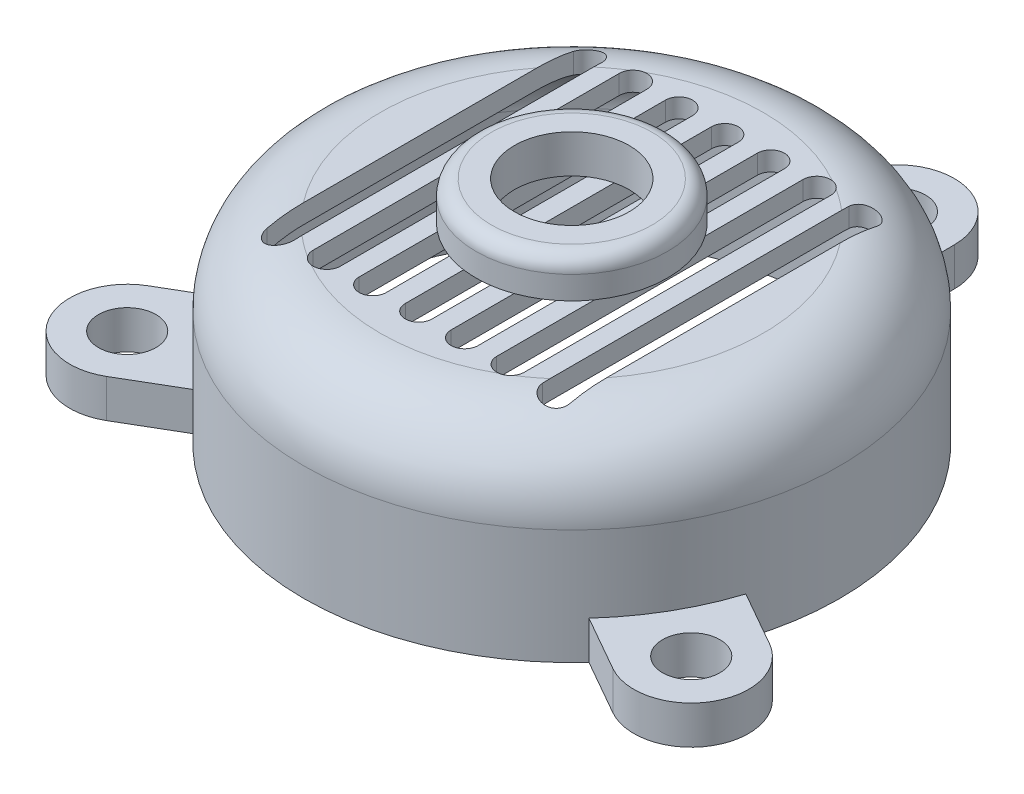
SolidWorks part; units mm, degrees
ref_plane "Front Plane" through (0, 0, 0) normal (0, 0, 1) x (1, 0, 0)
ref_plane "Top Plane" through (0, 0, 0) normal (0, 1, 0) x (1, 0, 0)
ref_plane "Right Plane" through (0, 0, 0) normal (1, 0, 0) x (0, 0, -1)
sketch "Sketch1" plane through (0, 0, 0) normal (0, 1, 0) x (1, 0, 0)
  circle A0 centre (0, 0) radius 3.5
  dimension "D1" = 7
extrude "Boss-Extrude1" add sketch "Sketch1" along normal mid plane 2.5
fillet "Fillet1" radius 1 1 edges at (0, 1.25, 3.5)
shell "Shell1" thickness 0.25
sketch "Sketch2" plane through (0, 1.25, 0) normal (0, 1, 0) x (1, 0, 0)
  line L0 (0, 2) -> (0, -2) construction
  line L1 (0.175, 2) -> (0.175, -2)
  line L2 (-0.175, 2) -> (-0.175, -2)
  line L3 (0.6, 2) -> (0.6, -2) construction
  line L4 (0.7768, 2) -> (0.7768, -2)
  line L5 (0.4232, 2) -> (0.4232, -2)
  line L6 (1.2, 2) -> (1.2, -2) construction
  line L7 (1.38, 2) -> (1.38, -2)
  line L8 (1.02, 2) -> (1.02, -2)
  line L9 (1.8, 2) -> (1.8, -2) construction
  line L10 (1.98, 2) -> (1.98, -2)
  line L11 (1.62, 2) -> (1.62, -2)
  arc A0 (0.175, 2) -> (-0.175, 2) centre (0, 2) ccw
  arc A1 (-0.175, -2) -> (0.175, -2) centre (0, -2) ccw
  arc A2 (0.7768, 2) -> (0.4232, 2) centre (0.6, 2) ccw
  arc A3 (0.4232, -2) -> (0.7768, -2) centre (0.6, -2) ccw
  arc A4 (1.38, 2) -> (1.02, 2) centre (1.2, 2) ccw
  arc A5 (1.02, -2) -> (1.38, -2) centre (1.2, -2) ccw
  arc A6 (1.98, 2) -> (1.62, 2) centre (1.8, 2) ccw
  arc A7 (1.62, -2) -> (1.98, -2) centre (1.8, -2) ccw
  point P3 (0, 0)
  point P10 (0.6, 0)
  point P15 (1.2, 0)
  point P22 (1.8, 0)
  dimension "D3" = 0.175
  dimension "D4" = 0.1768
  dimension "D5" = 0.18
  dimension "D6" = 0.18
  dimension "D7" = 0.6
  dimension "D1" = 4
  dimension "D2" = 2
  dimension "D8" = 0.6
  dimension "D9" = 0.6
extrude "Cut-Extrude2" cut sketch "Sketch2" against normal blind 10
mirror "Mirror1" about plane through (0, 0, 0) normal (1, 0, 0) of "Cut-Extrude2"
sketch "Sketch4" plane through (0, 1.25, 0) normal (0, 1, 0) x (1, 0, 0)
  circle A0 centre (0, 0) radius 1.25
  circle A1 centre (0, 0) radius 0.75
  dimension "D1" = 1.5
  dimension "D2" = 2.5
extrude "Boss-Extrude2" add sketch "Sketch4" along normal blind 0.5
fillet "Fillet2" radius 0.2 1 edges at (0, 1.75, 1.25)
sketch "Sketch5" plane through (0, -1.25, 0) normal (0, -1, 0) x (1, 0, 0)
  line L0 (4.0533, 1.4703) -> (3.3351, 1.0615)
  line L1 (4.0533, 1.4703) -> (3.3265, 1.0566) construction
  line L2 (-1007, 0) -> (-3.5, 0) construction
  line L3 (866.0254, 500) -> (-3.0311, -1.75) construction
  line L4 (3.3112, 2.7739) -> (2.5845, 2.3602)
  line L5 (0, 0) -> (50000, 0) construction
  line L6 (-3.7409, -2.1598) -> (-43301.2702, -25000) construction
  arc A0 (4.0533, 1.4703) -> (3.3112, 2.7739) centre (3.6823, 2.1221) ccw
  arc A1 (4.3196, 0) -> (3.3112, 2.7739) centre (0, 0) ccw construction
  circle A3 centre (0, 0) radius 3.5 construction
  arc A5 (3.03, 1.7518) -> (3.0349, 1.7434) centre (3.6823, 2.1221) ccw
  circle A6 centre (3.6823, 2.1221) radius 0.375
  arc A7 (3.3351, 1.0615) -> (2.5845, 2.3602) centre (0, 0) ccw
  arc A8 (-4.3196, 0) -> (-3.7409, -2.1598) centre (0, 0) ccw construction
  point P6 (3.2498, 1.0129)
  circle M2 centre (0, 0) radius 3.5
  dimension "D1" = 1.5
  dimension "D3" = 0.7274
  dimension "D5" = 0.75
  dimension "D6" = 1.5
  dimension "D4" = 30
extrude "Boss-Extrude3" add sketch "Sketch5" against normal blind 0.5 contours L0 A0 L4 A6 M2
pattern_circular "CirPattern1" count 3 over 360 about axis through (0, 0, 0) along (0, 1, 0) of "Boss-Extrude3"
